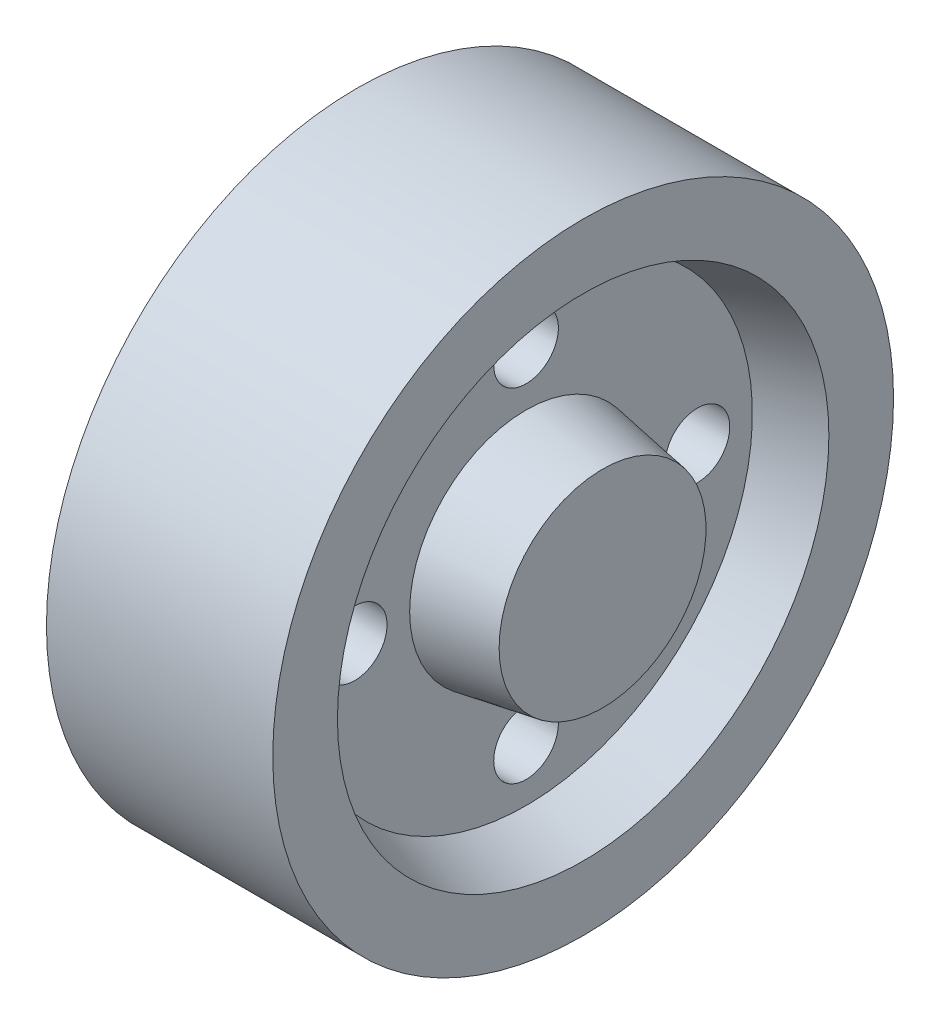
SolidWorks part; units mm, degrees
ref_plane "Front Plane" through (0, 0, 0) normal (0, 0, 1) x (1, 0, 0)
ref_plane "Top Plane" through (0, 0, 0) normal (0, 1, 0) x (1, 0, 0)
ref_plane "Right Plane" through (0, 0, 0) normal (1, 0, 0) x (0, 0, -1)
sketch "Sketch1" plane through (0, 0, 0) normal (0, 0, 1) x (1, 0, 0)
  line L0 (-20.5, 0) -> (39.8503, 0) construction
  line L1 (-20.5, 0) -> (-20.5, 16)
  line L2 (-20.5, 16) -> (-8.6678, 18)
  line L3 (-8.6678, 18) -> (-8.6678, 35)
  line L4 (-8.6678, 35) -> (-17.5, 38)
  line L5 (-17.5, 38) -> (-17.5, 48)
  line L6 (-17.5, 48) -> (17.5, 48)
  line L7 (0, 48) -> (0, 0) construction
  line L8 (20.5, 0) -> (20.5, 16)
  line L9 (20.5, 16) -> (8.6678, 18)
  line L10 (8.6678, 18) -> (8.6678, 35)
  line L11 (8.6678, 35) -> (17.5, 38)
  line L12 (17.5, 38) -> (17.5, 48)
  line L13 (-20.5, 0) -> (20.5, 0)
  dimension "D1" = 32
  dimension "D2" = 36
  dimension "D3" = 70
  dimension "D4" = 76
  dimension "D5" = 10
  dimension "D6" = 17.5
  dimension "D7" = 20.5
  dimension "D8" = 12
revolve "Revolve1" add sketch "Sketch1" angle 360 about L0
sketch "Sketch2" plane through (-8.6678, 0, 0) normal (-1, 0, 0) x (0, 0, 1)
  line L0 (0, -50.8753) -> (0, 50.8753) construction
  circle A0 centre (0, 0) radius 26.5 construction
  circle A1 centre (0, 26.5) radius 5
  circle A2 centre (26.5, 0) radius 5
  circle A3 centre (0, -26.5) radius 5
  circle A4 centre (-26.5, 0) radius 5
  circle A5 centre (0, 0) radius 10
  point P6 (0, 0)
  point P17 (0, 0)
  dimension "D1" = 53
  dimension "D2" = 10
  dimension "D4" = 20
  dimension "D3" = 4
extrude "Cut-Extrude1" cut sketch "Sketch2" against normal blind 26
